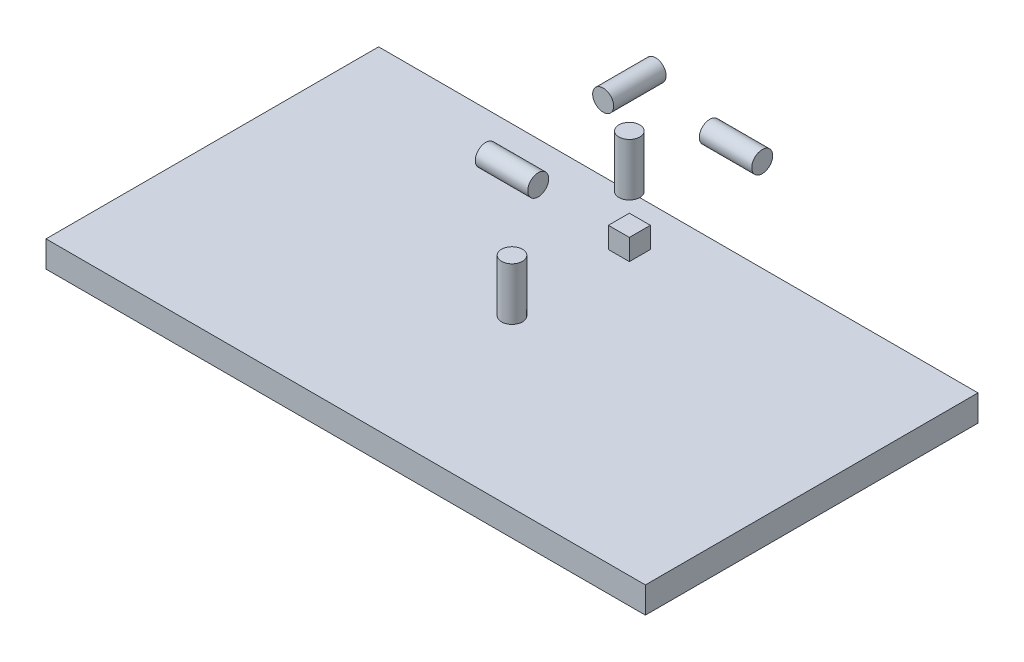
SolidWorks part; units mm, degrees
ref_plane "Front Plane" through (0, 0, 0) normal (0, 0, 1) x (1, 0, 0)
ref_plane "Top Plane" through (0, 0, 0) normal (0, 1, 0) x (1, 0, 0)
ref_plane "Right Plane" through (0, 0, 0) normal (1, 0, 0) x (0, 0, -1)
sketch "Sketch1" plane through (0, 0, 0) normal (0, 1, 0) x (1, 0, 0)
  line L1 (114.2559, -63.4021) -> (-114.2559, -63.4021)
  line L2 (114.2559, -63.4021) -> (114.2559, 63.4021)
  line L3 (114.2559, 63.4021) -> (-114.2559, 63.4021)
  line L4 (-114.2559, -63.4021) -> (-114.2559, 63.4021)
  line L5 (114.2559, -63.4021) -> (-114.2559, 63.4021) construction
  line L6 (114.2559, 63.4021) -> (-114.2559, -63.4021) construction
  point P0 (0, 0)
extrude "Boss-Extrude1" add sketch "Sketch1" against normal blind 10
sketch3d "3DSketch2"
  line L0 (0, 0, 0) -> (0, 48.2742, 0)
  line L1 (0, 48.2742, 0) -> (44.7451, 48.2742, 0)
  line L2 (44.7451, 48.2742, 0) -> (44.7451, 98.6121, 0)
  line L3 (44.7451, 98.6121, 0) -> (85.397, 98.6121, 0)
  point P7 (44.7451, 73.4431, 0)
sketch "Sketch2" plane through (0, 0, 0) normal (0, 1, 0) x (1, 0, 0)
  circle A0 centre (0, 0) radius 4
  dimension "D1" = 8
extrude "Boss-Extrude2" add sketch "Sketch2" along normal blind 20
sketch "Sketch3" plane through (0, 0, 0) normal (1, 0, 0) x (0, 0, -1)
  circle A0 centre (0, 48.2742) radius 4
  dimension "D1" = 8
extrude "Boss-Extrude3" add sketch "Sketch3" along normal mid plane 20 separate body
ref_plane "Plane1" through (44.7451, 0, 0) normal (1, 0, 0) x (0, 0, -1)
sketch "Sketch4" plane through (44.7451, 0, 0) normal (1, 0, 0) x (0, 0, -1)
  line L1 (4, 44.2742) -> (-4, 44.2742)
  line L2 (4, 44.2742) -> (4, 52.2742)
  line L3 (4, 52.2742) -> (-4, 52.2742)
  line L4 (-4, 44.2742) -> (-4, 52.2742)
  line L5 (4, 44.2742) -> (-4, 52.2742) construction
  line L6 (4, 52.2742) -> (-4, 44.2742) construction
  point P0 (0, 48.2742)
  dimension "D1" = 8
extrude "Boss-Extrude4" add sketch "Sketch4" along normal mid plane 8 separate body
ref_plane "Plane2" through (0, 73.4431, 0) normal (0, 1, 0) x (1, 0, 0)
sketch "Sketch5" plane through (0, 73.4431, 0) normal (0, 1, 0) x (1, 0, 0)
  circle A0 centre (44.7451, 0) radius 4
  dimension "D1" = 8
extrude "Boss-Extrude5" add sketch "Sketch5" along normal mid plane 20 separate body
sketch "Sketch7" plane through (0, 0, 0) normal (0, 0, 1) x (1, 0, 0)
  circle A0 centre (44.7451, 98.6121) radius 4
  dimension "D1" = 8
extrude "Boss-Extrude6" add sketch "Sketch7" along normal mid plane 20 separate body
ref_plane "Plane3" through (85.397, 0, 0) normal (1, 0, 0) x (0, 0, -1)
sketch "Sketch9" plane through (85.397, 0, 0) normal (1, 0, 0) x (0, 0, -1)
  circle A0 centre (0, 98.6121) radius 4
  dimension "D1" = 8
extrude "Boss-Extrude7" add sketch "Sketch9" along normal mid plane 20 separate body
